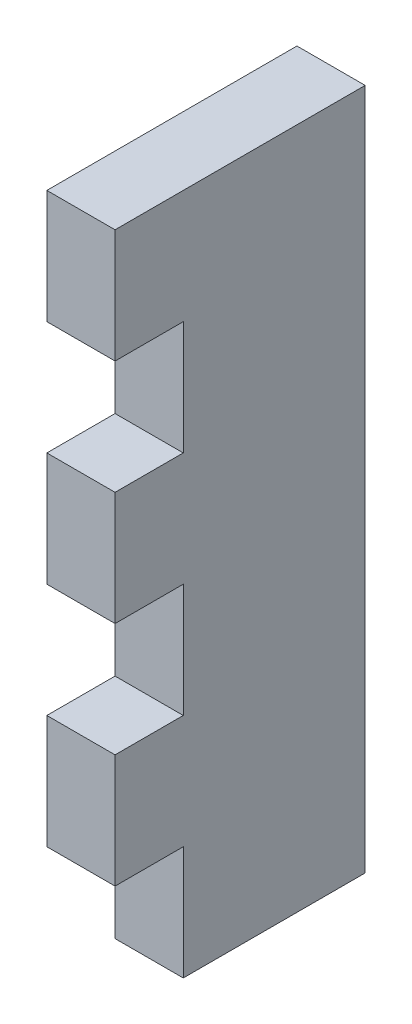
SolidWorks part; units mm, degrees
ref_plane "Front Plane" through (0, 0, 0) normal (0, 0, 1) x (1, 0, 0)
ref_plane "Top Plane" through (0, 0, 0) normal (0, 1, 0) x (1, 0, 0)
ref_plane "Right Plane" through (0, 0, 0) normal (1, 0, 0) x (0, 0, -1)
sketch "Sketch1" plane through (0, 0, 0) normal (1, 0, 0) x (0, 0, -1)
  line L1 (-5.5, 15) -> (5.5, 15)
  line L2 (-5.5, 15) -> (-5.5, -15)
  line L3 (-5.5, -15) -> (5.5, -15)
  line L4 (5.5, 15) -> (5.5, -15)
  line L5 (-5.5, 15) -> (5.5, -15) construction
  line L6 (-5.5, -15) -> (5.5, 15) construction
  point P0 (0, 0)
  dimension "D1" = 30
  dimension "D2" = 11
extrude "Boss-Extrude1" add sketch "Sketch1" along normal blind 3
sketch "Sketch2" plane through (3, 0, 0) normal (1, 0, 0) x (0, 0, -1)
  line L6 (-5.5, -10) -> (-2.5, -10)
  line L7 (-5.5, 15) -> (-5.5, -15) construction
  line L8 (-5.5, 10) -> (-2.5, 10)
  line L9 (-5.5, 10) -> (-5.5, 5)
  line L10 (-5.5, 5) -> (-2.5, 5)
  line L11 (-2.5, 10) -> (-2.5, 5)
  line L12 (5.5, 15) -> (-5.5, 15) construction
  line L14 (-5.5, 0) -> (-2.5, 0)
  line L15 (-5.5, 0) -> (-5.5, -5)
  line L16 (-5.5, -5) -> (-2.5, -5)
  line L17 (-2.5, 0) -> (-2.5, -5)
  line L18 (-5.5, -10) -> (-5.5, -15)
  line L19 (-5.5, -15) -> (-2.5, -15)
  line L20 (-2.5, -10) -> (-2.5, -15)
  dimension "D1" = 3
  dimension "D2" = 5
  dimension "D3" = 5
  dimension "D4" = 5
  dimension "D5" = 5
extrude "Cut-Extrude1" cut sketch "Sketch2" against normal blind 3
hole_wizard "#4 Clearance Hole1" positions "Sketch3" profile "Sketch4" hole size "#4" standard "ANSI Inch"
sketch "Sketch3" plane through (3, 0, 0) normal (1, 0, 0) x (0, 0, -1)
  line L0 (5.5, -15) -> (5.5, 15) construction
  line L1 (-2.5, -15) -> (5.5, -15) construction
  line L2 (5.5, 15) -> (-5.5, 15) construction
  point P0 (1.5, 11.5)
  point P2 (1.5, -11.5)
  dimension "D1" = 4
  dimension "D2" = 3.5
  dimension "D3" = 3.5
sketch "Sketch4" plane through (3, 11.5, -1.5) normal (0, 1, 0) x (0, 0, -1)
  line L0 (0, 0) -> (0, 3)
  line L1 (0, 3) -> (1.6319, 3)
  line L2 (1.6319, 3) -> (1.6319, 0)
  line L5 (1.6319, 0) -> (0, 0)
  line L11 (0, -6.35) -> (0, 107.95) construction
  dimension "Thru Hole Dia." = 3.2639
  dimension "Thru Hole Depth" = 3
equation "\"D2@Sketch1\"=8+3"
equation "\"D3@Sketch3\"=\"D2@Sketch3\""
